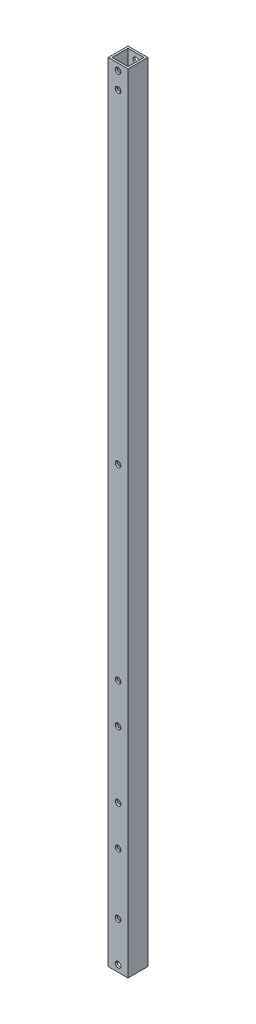
SolidWorks part; units mm, degrees
material "5052-H34"
ref_plane "正面" through (0, 0, 0) normal (0, 0, 1) x (1, 0, 0)
ref_plane "平面" through (0, 0, 0) normal (0, 1, 0) x (1, 0, 0)
ref_plane "右側面" through (0, 0, 0) normal (1, 0, 0) x (0, 0, -1)
sketch "ｽｹｯﾁ1" plane through (0, 0, 0) normal (0, 1, 0) x (1, 0, 0)
  line L1 (0, 0) -> (15, 0)
  line L2 (0, 0) -> (0, 15)
  line L3 (0, 15) -> (15, 15)
  line L4 (15, 0) -> (15, 15)
  dimension "D1" = 15
  dimension "D2" = 15
extrude "押し出し-薄板1" add sketch "ｽｹｯﾁ1" along normal blind 595 thin thin type one direction reverse wall 1.5
sketch "ｽｹｯﾁ3" plane through (0, 0, 0) normal (0, 0, 1) x (1, 0, 0)
  line L0 (7.5, 595) -> (7.5, 0) construction
  line L1 (0, 595) -> (15, 595) construction
  line L2 (0, 0) -> (15, 0) construction
  circle A3 centre (7.5, 81) radius 2.15
  circle A4 centre (7.5, 111) radius 2.15
  circle A5 centre (7.5, 161) radius 2.15
  circle A6 centre (7.5, 191) radius 2.15
  circle A7 centre (7.5, 5) radius 2.15
  circle A8 centre (7.5, 35) radius 2.15
  dimension "D1" = 4.3
  dimension "D2" = 46
  dimension "D3" = 30
  dimension "D4" = 30
  dimension "D5" = 50
  dimension "D6" = 30
  dimension "D7" = 5
extrude "ｶｯﾄ - 押し出し2" cut sketch "ｽｹｯﾁ3" against normal up to surface (15 mm away) up to face at (7.5, 297.5, -15)
sketch "ｽｹｯﾁ4" plane through (15, 0, 0) normal (0, 0, -1) x (-1, 0, 0)
  line L0 (7.5, 595) -> (7.5, 577.5) construction
  line L2 (0, 595) -> (15, 595) construction
  line L3 (7.5, 602.5) -> (7.5, 332.5) construction
  circle A0 centre (7.5, 577.5) radius 2.15
  circle A2 centre (7.5, 590) radius 2.15
  circle A3 centre (7.5, 332.5) radius 2.15
  dimension "D1" = 4.3
  dimension "D6" = 4.3
  dimension "D2" = 5
  dimension "D3" = 12.5
  dimension "D4" = 7.5
  dimension "D5" = 270
extrude "ｶｯﾄ - 押し出し3" cut sketch "ｽｹｯﾁ4" along normal through all
